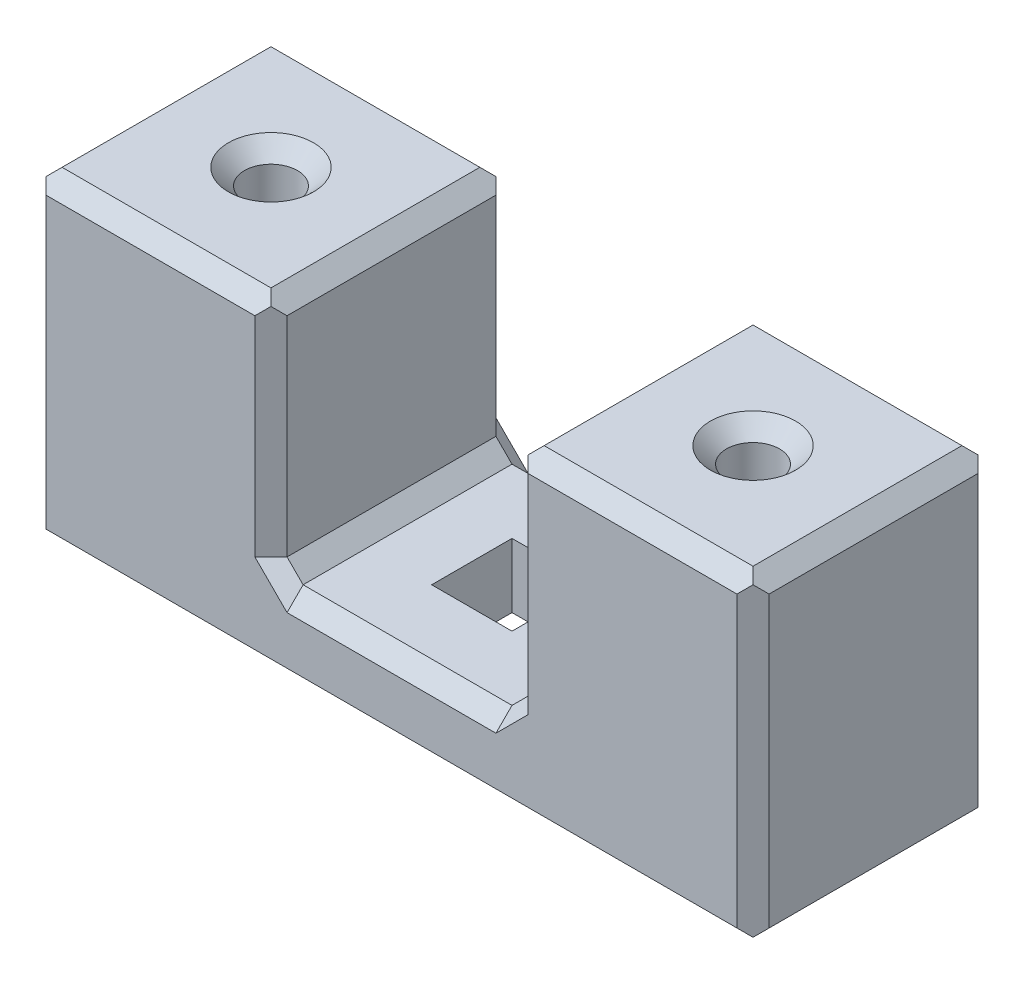
SolidWorks part; units mm, degrees
material "ABS"
ref_plane "Front Plane" through (0, 0, 0) normal (0, 0, 1) x (1, 0, 0)
ref_plane "Top Plane" through (0, 0, 0) normal (0, 1, 0) x (1, 0, 0)
ref_plane "Right Plane" through (0, 0, 0) normal (1, 0, 0) x (0, 0, -1)
sketch "Sketch1" plane through (0, 0, 0) normal (0, 1, 0) x (1, 0, 0)
  line L0 (0, 7.5) -> (45, 7.5) construction
  line L1 (0, 0) -> (45, 0)
  line L2 (0, 0) -> (0, 15)
  line L3 (0, 15) -> (45, 15)
  line L4 (45, 0) -> (45, 15)
  line L6 (20, 10) -> (25, 10)
  line L7 (20, 10) -> (20, 5)
  line L8 (20, 5) -> (25, 5)
  line L9 (25, 10) -> (25, 5)
  point P16 (22.5, 0)
  dimension "D1" = 15
  dimension "D2" = 45
  dimension "D7" = 5
  dimension "D8" = 5
  dimension "D9" = 5
  dimension "D10" = 20
extrude "Boss-Extrude1" add sketch "Sketch1" along normal blind 20
sketch "Sketch2" plane through (0, 0, 0) normal (0, 0, 1) x (1, 0, 0)
  line L0 (0, 20) -> (45, 20) construction
  line L1 (15, 20) -> (30, 20)
  line L2 (15, 20) -> (15, 5)
  line L3 (15, 5) -> (30, 5)
  line L4 (30, 20) -> (30, 5)
  line L5 (0, 0) -> (45, 0) construction
  line L6 (0, 20) -> (0, 0) construction
  line L7 (45, 20) -> (45, 0) construction
  dimension "D1" = 5
  dimension "D2" = 15
  dimension "D3" = 15
extrude "Cut-Extrude1" cut sketch "Sketch2" against normal blind 20
sketch "Sketch3" plane through (0, 20, 0) normal (0, 1, 0) x (1, 0, 0)
  line L0 (1, 7.5) -> (44, 7.5) construction
  line L6 (0, 15) -> (0, 0) construction
  line L8 (0, 0) -> (15, 0) construction
  circle A0 centre (37.5, 7.5) radius 1.65
  circle A1 centre (7.5, 7.5) radius 1.65
  dimension "D1" = 3.3
  dimension "D2" = 3.3
  dimension "D3" = 7.5
  dimension "D4" = 30
  dimension "D5" = 7.5
extrude "Cut-Extrude2" cut sketch "Sketch3" against normal blind 10
chamfer "Chamfer2" distance 1 angle 45 18 edges at (45, 20, -7.5) (37.5, 20, 0) (30, 20, -7.5) (37.5, 20, -15) (37.5, 20, -5.85) (0, 20, -7.5) (7.5, 20, -15) (15, 20, -7.5) (7.5, 20, 0) (7.5, 20, -5.85) (25, 0, -7.5) (22.5, 0, -5) (20, 0, -7.5) (22.5, 0, -10) (22.5, 0, 0) (45, 0, -7.5) (22.5, 0, -15) (0, 0, -7.5)
chamfer "Chamfer3" distance 1 angle 45 12 edges at (45, 10, 0) (45, 10, -15) (30, 12, 0) (30, 12, -15) (22.5, 5, 0) (30, 5, -7.5) (15, 12, 0) (15, 5, -7.5) (15, 12, -15) (22.5, 5, -15) (0, 10, -15) (0, 10, 0)
